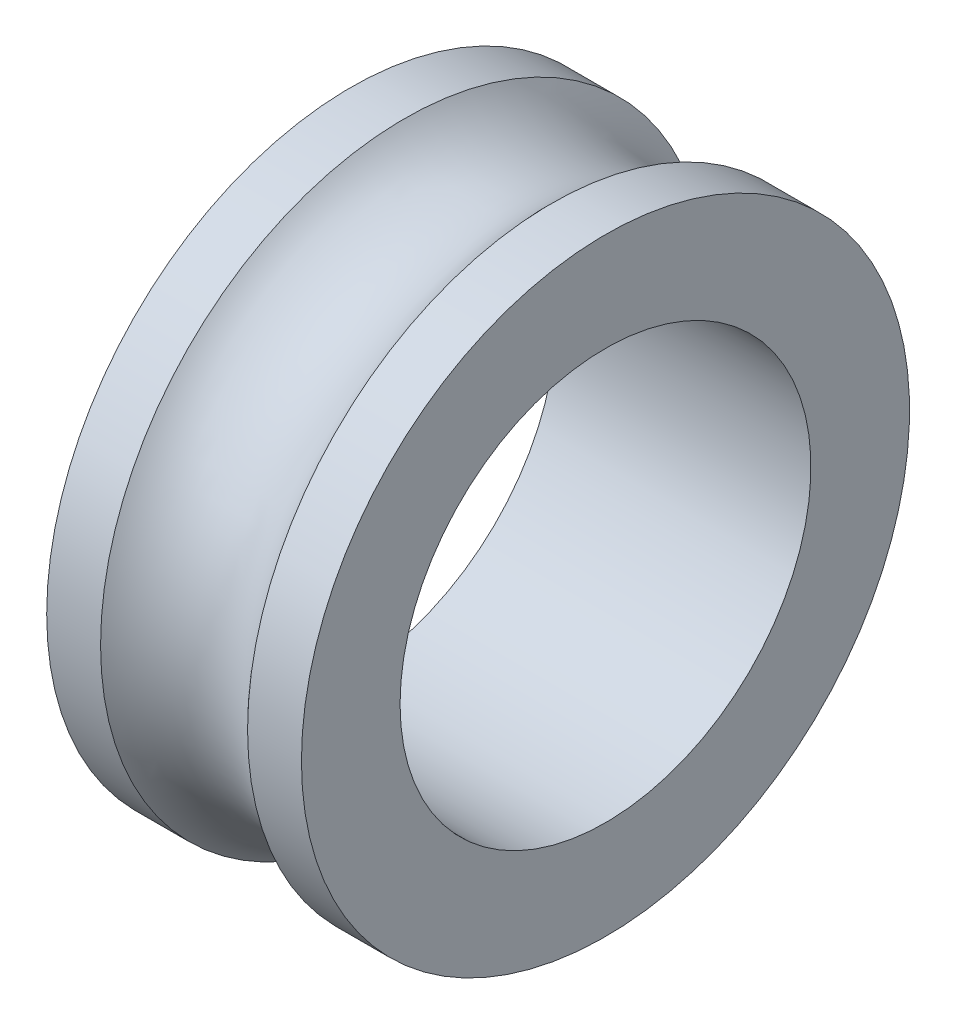
SolidWorks part; units mm, degrees
ref_plane "Front Plane" through (0, 0, 0) normal (0, 0, 1) x (1, 0, 0)
ref_plane "Top Plane" through (0, 0, 0) normal (0, 1, 0) x (1, 0, 0)
ref_plane "Right Plane" through (0, 0, 0) normal (1, 0, 0) x (0, 0, -1)
sketch "Sketch1" plane through (0, 0, 0) normal (0, 0, 1) x (1, 0, 0)
  line L0 (0, 0) -> (0, 25) construction
  line L1 (-15.5, 37) -> (-8.9443, 37)
  line L2 (-15.5, 37) -> (-15.5, 25)
  line L3 (-15.5, 25) -> (15.5, 25)
  line L4 (15.5, 37) -> (15.5, 25)
  line L5 (8.9443, 37) -> (15.5, 37)
  line L6 (0, 0) -> (56.7106, 0) construction
  arc A0 (-8.9443, 37) -> (8.9443, 37) centre (0, 45) ccw
  dimension "D6" = 12
  dimension "D1" = 25
  dimension "D2" = 37
  dimension "D3" = 31
  dimension "D4" = 15.5
  dimension "D5" = 8
revolve "Revolve1" add sketch "Sketch1" angle 360 about L6
